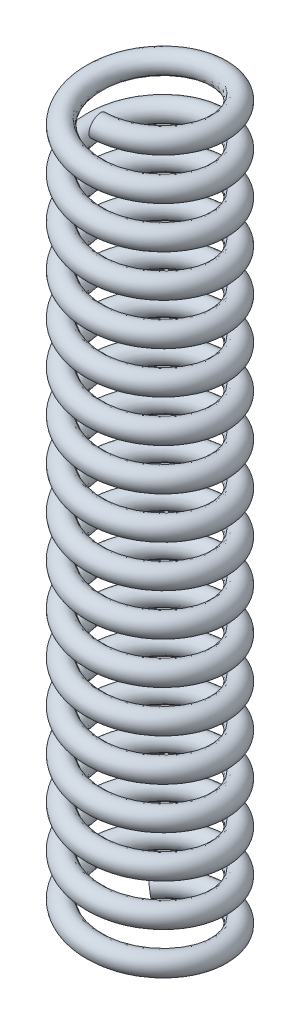
SolidWorks part; units mm, degrees
ref_plane "Front Plane" through (0, 0, 0) normal (0, 0, 1) x (1, 0, 0)
ref_plane "Top Plane" through (0, 0, 0) normal (0, 1, 0) x (1, 0, 0)
ref_plane "Right Plane" through (0, 0, 0) normal (1, 0, 0) x (0, 0, -1)
sketch "Sketch4" plane through (0, 0, 0) normal (0, 1, 0) x (1, 0, 0)
  circle A0 centre (0, 0) radius 1.5
  dimension "D1" = 3
curve "Helix/Spiral1" pitch 1 height 17.6 turns 17.6
sweep "Sweep1" add path "Helix/Spiral1" circular profile diameter 0.5 parameters "D3"=0.5
